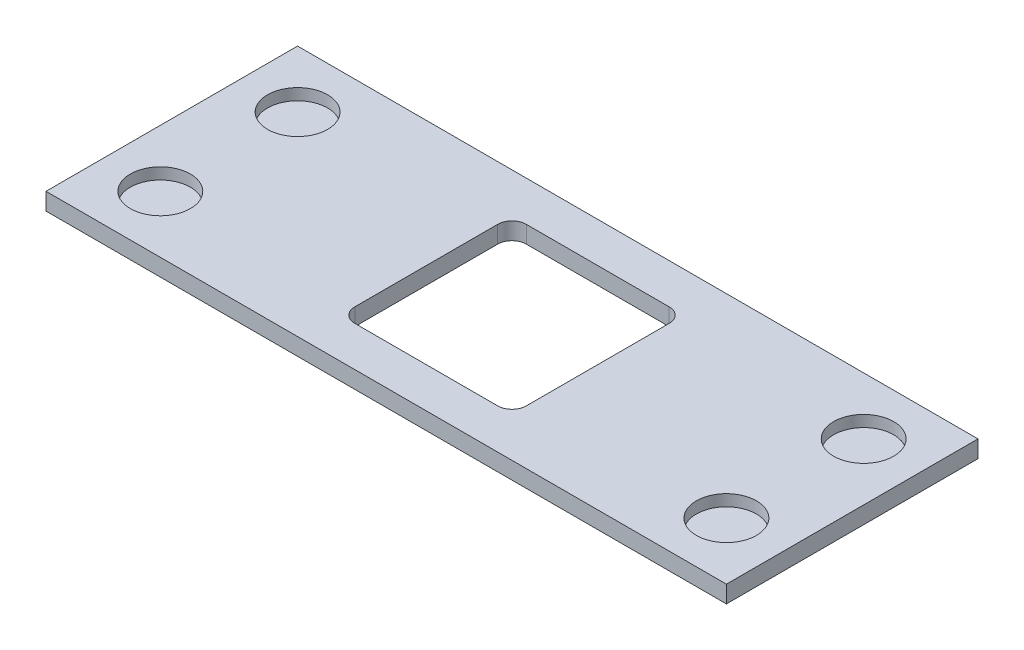
SolidWorks part; units mm, degrees
ref_plane "Plano frontal" through (0, 0, 0) normal (0, 0, 1) x (1, 0, 0)
ref_plane "Plano superior" through (0, 0, 0) normal (0, 1, 0) x (1, 0, 0)
ref_plane "Plano direito" through (0, 0, 0) normal (1, 0, 0) x (0, 0, -1)
sketch "Esboço1" plane through (0, 0, 0) normal (0, 1, 0) x (1, 0, 0)
  line L1 (-59.5, 22) -> (59.5, 22)
  line L2 (-59.5, 22) -> (-59.5, -22)
  line L3 (-59.5, -22) -> (59.5, -22)
  line L4 (59.5, 22) -> (59.5, -22)
  line L5 (-59.5, 22) -> (59.5, -22) construction
  line L6 (-59.5, -22) -> (59.5, 22) construction
  point P0 (0, 0)
  dimension "D1" = 119
  dimension "D2" = 44
extrude "Extrusão1" add sketch "Esboço1" along normal blind 3
sketch "Esboço2" plane through (0, 3, 0) normal (0, 1, 0) x (1, 0, 0)
  line L0 (59.5, 22) -> (-59.5, 22) construction
  line L1 (-59.5, 22) -> (-59.5, -22) construction
  circle A0 centre (-49.5, 12) radius 5.25
  dimension "D1" = 10.5
  dimension "D2" = 10
  dimension "D3" = 10
extrude "Extrusão2" cut sketch "Esboço2" against normal blind 2
mirror "Espelhar1" about plane through (0, 0, 0) normal (1, 0, 0) of "Extrusão2"
mirror "Espelhar2" about plane through (0, 0, 0) normal (0, 0, 1) of "Espelhar1", "Extrusão2"
sketch "Esboço3" plane through (0, 3, 0) normal (0, 1, 0) x (1, 0, 0)
  line L1 (-12.5, 15) -> (12.5, 15)
  line L2 (-15, 12.5) -> (-15, -12.5)
  line L3 (-12.5, -15) -> (12.5, -15)
  line L4 (15, 12.5) -> (15, -12.5)
  line L5 (-15, 15) -> (15, -15) construction
  line L6 (-15, -15) -> (15, 15) construction
  arc A0 (-12.5, 15) -> (-15, 12.5) centre (-12.5, 12.5) ccw
  arc A1 (-15, -12.5) -> (-12.5, -15) centre (-12.5, -12.5) ccw
  arc A2 (12.5, -15) -> (15, -12.5) centre (12.5, -12.5) ccw
  arc A3 (12.5, 15) -> (15, 12.5) centre (12.5, 12.5) cw
  point P0 (0, 0)
  dimension "D3" = 2.5
  dimension "D1" = 30
  dimension "D2" = 30
extrude "Extrusão3" cut sketch "Esboço3" against normal blind 3
